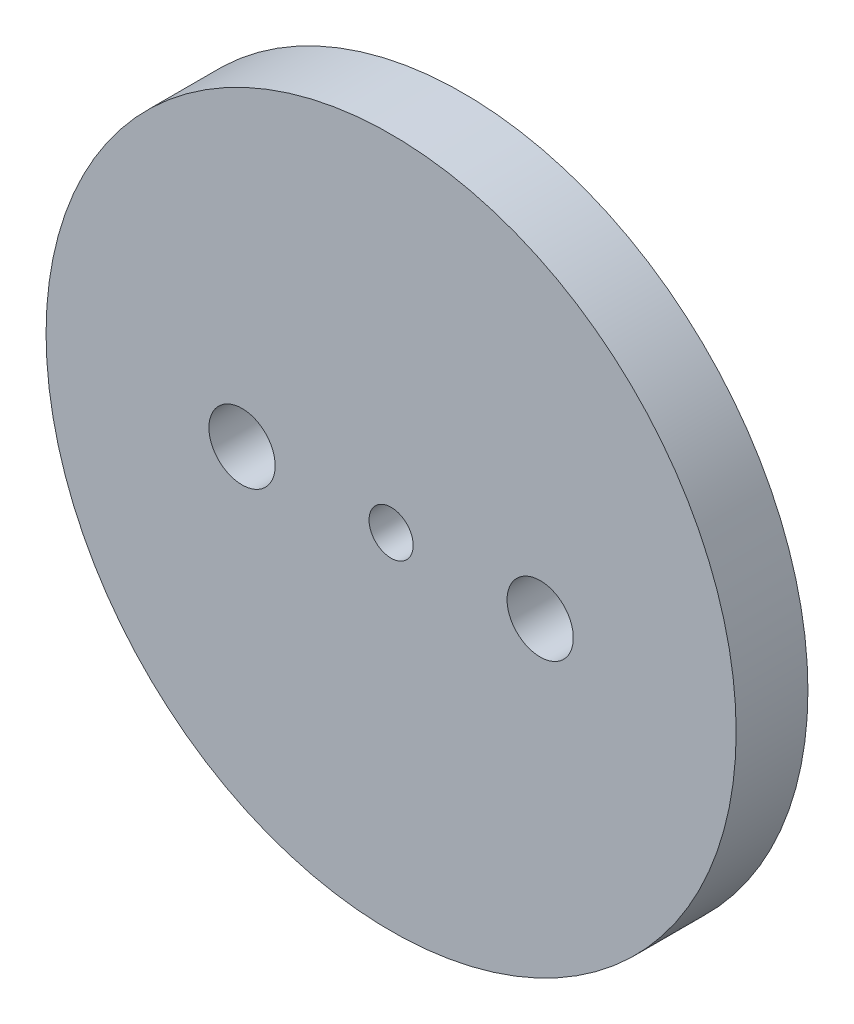
SolidWorks part; units mm, degrees
ref_plane "Front Plane" through (0, 0, 0) normal (0, 0, 1) x (1, 0, 0)
ref_plane "Top Plane" through (0, 0, 0) normal (0, 1, 0) x (1, 0, 0)
ref_plane "Right Plane" through (0, 0, 0) normal (1, 0, 0) x (0, 0, -1)
sketch "Sketch1" plane through (0, 0, 0) normal (0, 0, 1) x (1, 0, 0)
  line L0 (0, 27) -> (0, 17.7343) construction
  circle A0 centre (0, 0) radius 62.5
  circle A1 centre (0, 0) radius 27 construction
  circle A2 centre (27, 0) radius 6
  circle A3 centre (-27, 0) radius 6
  dimension "D1" = 125
  dimension "D2" = 54
  dimension "D3" = 12
extrude "Boss-Extrude1" add sketch "Sketch1" along normal blind 13
sketch "Sketch2" plane through (0, 0, 13) normal (0, 0, 1) x (1, 0, 0)
  circle A0 centre (0, 0) radius 4
  dimension "D1" = 8
extrude "Cut-Extrude1" cut sketch "Sketch2" against normal blind 13
